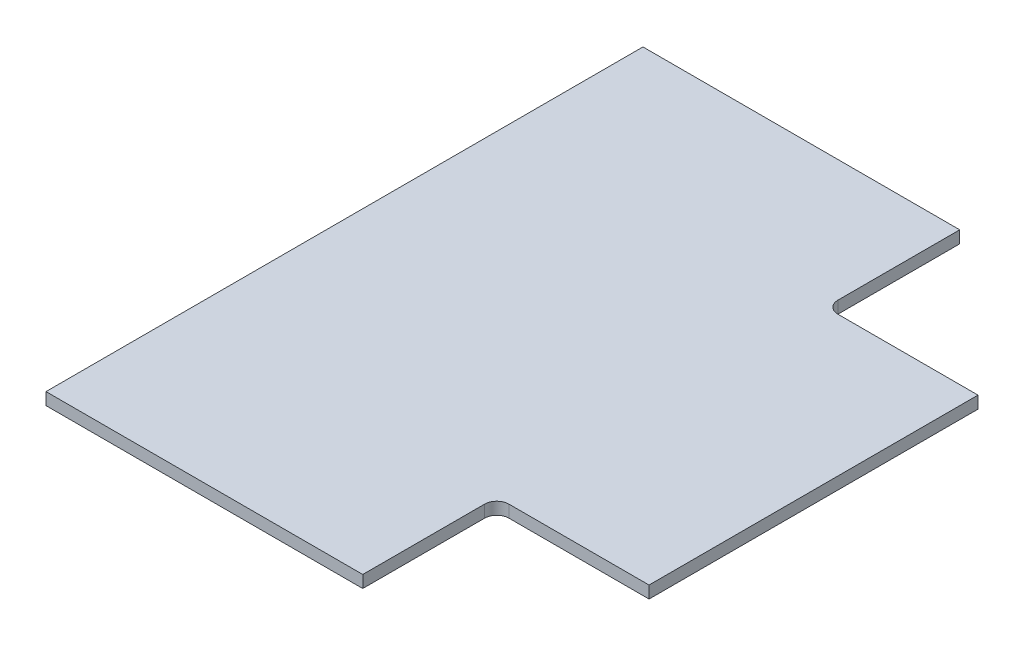
SolidWorks part; units mm, degrees
ref_plane "Alzado" through (0, 0, 0) normal (0, 0, 1) x (1, 0, 0)
ref_plane "Planta" through (0, 0, 0) normal (0, 1, 0) x (1, 0, 0)
ref_plane "Vista lateral" through (0, 0, 0) normal (1, 0, 0) x (0, 0, -1)
sketch "Croquis1" plane through (0, 0, 0) normal (0, 1, 0) x (1, 0, 0)
  line L0 (0, -49) -> (0, 49)
  line L1 (0, 49) -> (52, 49)
  line L2 (52, 49) -> (52, 29)
  line L3 (54, 27) -> (77, 27)
  line L4 (77, 27) -> (77, -27)
  line L5 (77, -27) -> (54, -27)
  line L6 (52, -29) -> (52, -49)
  line L7 (52, -49) -> (0, -49)
  arc A0 (52, 29) -> (54, 27) centre (54, 29) ccw
  arc A1 (54, -27) -> (52, -29) centre (54, -29) ccw
  point P10 (52, 27)
  point P13 (52, -27)
  point P14 (0, 0)
  dimension "D7" = 2
  dimension "D8" = 2
  dimension "D1" = 52
  dimension "D2" = 52
  dimension "D3" = 98
  dimension "D4" = 22
  dimension "D5" = 22
  dimension "D6" = 25
extrude "Saliente-Extruir1" add sketch "Croquis1" along normal blind 2
